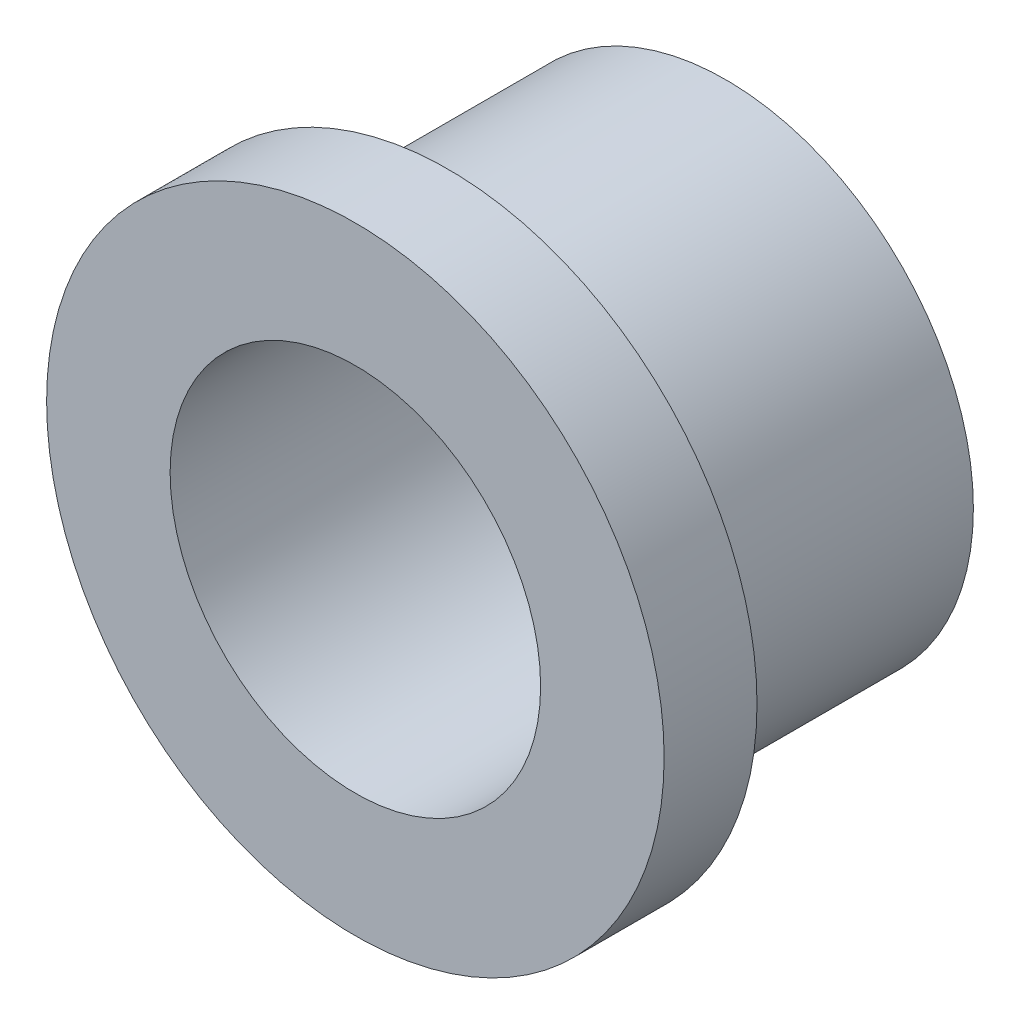
SolidWorks part; units mm, degrees
material "Brass"
ref_plane "Front" through (0, 0, 0) normal (0, 0, 1) x (1, 0, 0)
ref_plane "Top" through (0, 0, 0) normal (0, 1, 0) x (1, 0, 0)
ref_plane "Right" through (0, 0, 0) normal (1, 0, 0) x (0, 0, -1)
sketch "Sketch2" plane through (0, 0, 0) normal (1, 0, 0) x (0, 0, -1)
  line L0 (0, 0) -> (0, 4.7625) construction
  line L1 (0, 4.7625) -> (0, 7.9375)
  line L2 (0, 7.9375) -> (2.3876, 7.9375)
  line L3 (2.3876, 7.9375) -> (2.3876, 6.3627)
  line L4 (2.3876, 6.3627) -> (9.525, 6.3627)
  line L5 (9.525, 6.3627) -> (9.525, 4.7625)
  line L6 (9.525, 4.7625) -> (0, 4.7625)
  line L7 (0, 0) -> (9.525, 0) construction
  line L8 (9.525, 0) -> (9.525, 4.7625) construction
  dimension "D1" = 2.3876
  dimension "D2" = 9.525
  dimension "D3" = 12.7254
  dimension "D4" = 9.525
  dimension "D5" = 15.875
revolve "Revolve1" add sketch "Sketch2" angle 360 about L7
